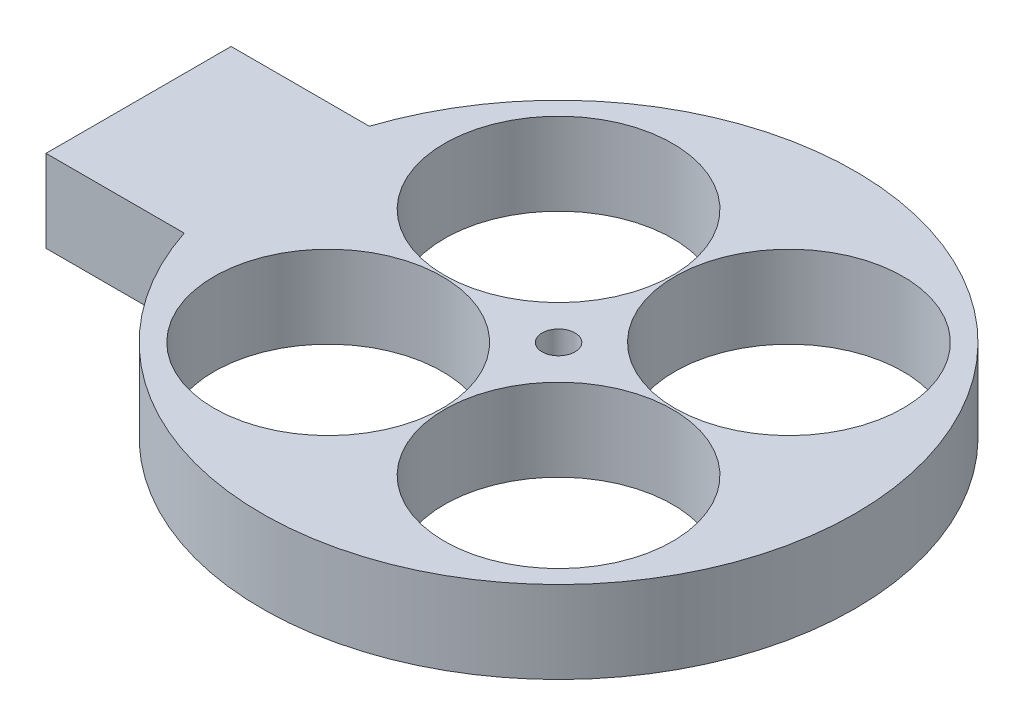
SolidWorks part; units mm, degrees
material "Nylon 101"
ref_plane "Alzado" through (0, 0, 0) normal (0, 0, 1) x (1, 0, 0)
ref_plane "Planta" through (0, 0, 0) normal (0, 1, 0) x (1, 0, 0)
ref_plane "Vista lateral" through (0, 0, 0) normal (1, 0, 0) x (0, 0, -1)
ref_plane "Plane2" through (0, -2, 0) normal (0, 1, 0) x (1, 0, 0)
sketch "Sketch1" plane through (0, -2, 0) normal (0, 1, 0) x (1, 0, 0)
  circle A0 centre (0, 0) radius 14.4196
  circle A1 centre (5.6, 5.6) radius 5.55
  circle A2 centre (-5.6, 5.6) radius 5.55
  circle A3 centre (-5.6, -5.6) radius 5.55
  circle A4 centre (5.6, -5.6) radius 5.55
  circle A5 centre (0, 0) radius 0.8
extrude "Placa_cabezal" add sketch "Sketch1" along normal blind 4
sketch "Sketch2" plane through (0, -2, 0) normal (0, 1, 0) x (1, 0, 0)
  line L0 (-20.4196, -4.5) -> (-12.9196, -4.5)
  line L1 (-12.9196, -4.5) -> (-12.9196, 4.5)
  line L2 (-12.9196, 4.5) -> (-20.4196, 4.5)
  line L3 (-20.4196, 4.5) -> (-20.4196, -4.5)
extrude "Pata_al_hueso" add sketch "Sketch2" along normal blind 4
